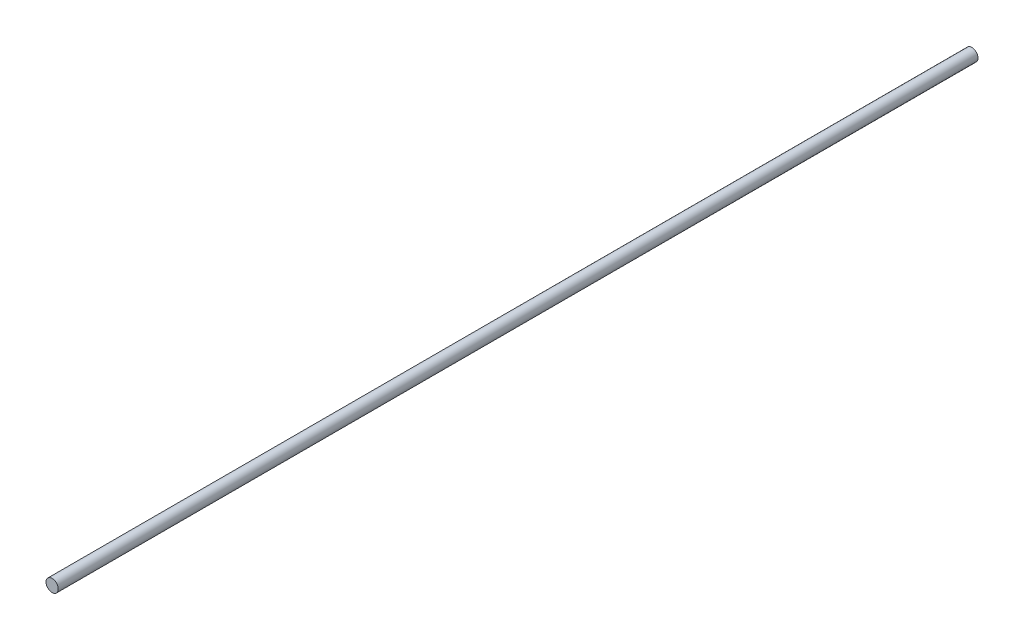
SolidWorks part; units mm, degrees
material "Stainless Steel"
ref_plane "Front" through (0, 0, 0) normal (0, 0, 1) x (1, 0, 0)
ref_plane "Top" through (0, 0, 0) normal (0, 1, 0) x (1, 0, 0)
ref_plane "Right" through (0, 0, 0) normal (1, 0, 0) x (0, 0, -1)
sketch "Sketch1" plane through (0, 0, 0) normal (0, 0, 1) x (1, 0, 0)
  circle A0 centre (0, 0) radius 1.5875
  dimension "D1" = 3.175
extrude "Boss-Extrude1" add sketch "Sketch1" along normal mid plane 238.125
